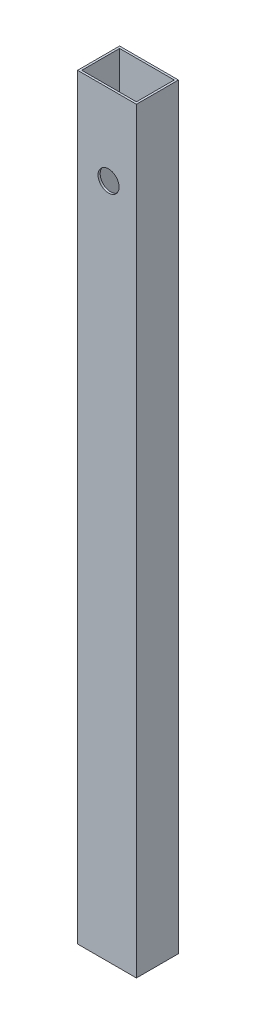
SolidWorks part; units mm, degrees
material "Plain Carbon Steel"
ref_plane "Front Plane" through (0, 0, 0) normal (0, 0, 1) x (1, 0, 0)
ref_plane "Top Plane" through (0, 0, 0) normal (0, 1, 0) x (1, 0, 0)
ref_plane "Right Plane" through (0, 0, 0) normal (1, 0, 0) x (0, 0, -1)
sketch "Sketch1" plane through (0, 0, 0) normal (0, 1, 0) x (1, 0, 0)
  line L1 (-17.78, 12.7) -> (17.78, 12.7)
  line L2 (-17.78, 12.7) -> (-17.78, -12.7)
  line L3 (-17.78, -12.7) -> (17.78, -12.7)
  line L4 (17.78, 12.7) -> (17.78, -12.7)
  line L5 (-17.78, 12.7) -> (17.78, -12.7) construction
  line L6 (-17.78, -12.7) -> (17.78, 12.7) construction
  point P0 (0, 0)
  dimension "D1" = 35.56
  dimension "D2" = 25.4
extrude "Boss-Extrude1" add sketch "Sketch1" along normal blind 457.2
sketch "Sketch2" plane through (0, 457.2, 0) normal (0, 1, 0) x (1, 0, 0)
  line L9 (16.51, -11.43) -> (16.51, 11.43)
  line L10 (16.51, 11.43) -> (-16.51, 11.43)
  line L11 (-16.51, 11.43) -> (-16.51, -11.43)
  line L12 (-16.51, -11.43) -> (16.51, -11.43)
  line L13 (16.51, -11.43) -> (16.51, 11.43)
  line L14 (16.51, 11.43) -> (-16.51, 11.43)
  line L15 (-16.51, 11.43) -> (-16.51, -11.43)
  line L16 (-16.51, -11.43) -> (16.51, -11.43)
  dimension "D1" = 1.27
extrude "Cut-Extrude1" cut sketch "Sketch2" against normal through all
sketch "Sketch3" plane through (0, 0, 12.7) normal (0, 0, 1) x (1, 0, 0)
  circle A0 centre (0.9548, 408.6434) radius 6.35
  dimension "D1" = 12.7
extrude "Cut-Extrude2" cut sketch "Sketch3" against normal up to next
sketch "Sketch4" plane through (0, 0, -12.7) normal (0, 0, -1) x (-1, 0, 0)
  circle A0 centre (-0.9548, 408.6434) radius 6.35
  dimension "D1" = 12.7
extrude "Cut-Extrude3" cut sketch "Sketch4" against normal up to next
